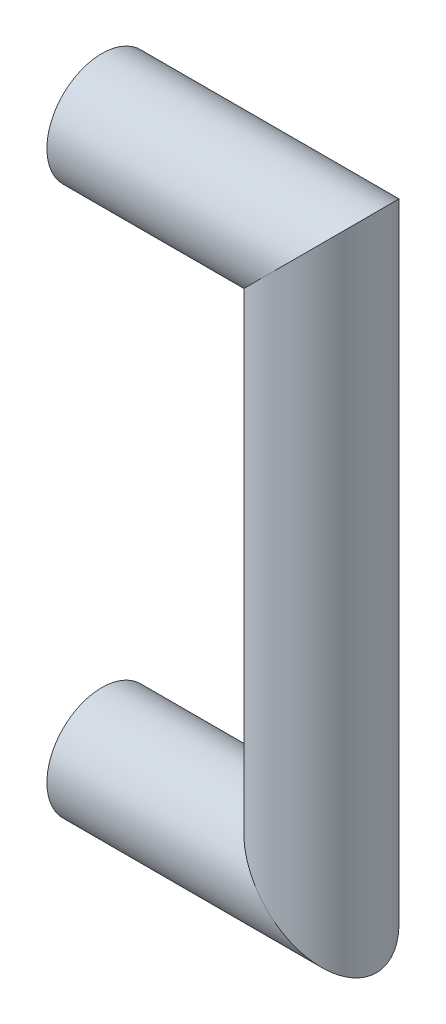
SolidWorks part; units mm, degrees
ref_plane "Front Plane" through (0, 0, 0) normal (0, 0, 1) x (1, 0, 0)
ref_plane "Top Plane" through (0, 0, 0) normal (0, 1, 0) x (1, 0, 0)
ref_plane "Right Plane" through (0, 0, 0) normal (1, 0, 0) x (0, 0, -1)
sketch "Sketch1" plane through (0, 0, 0) normal (1, 0, 0) x (0, 0, -1)
  circle A0 centre (0, 0) radius 10
  dimension "D1" = 20
sketch "Sketch3" plane through (0, 0, 0) normal (0, 0, 1) x (1, 0, 0)
  line L0 (0, 0) -> (40, 0)
  line L1 (40, 0) -> (40, -100)
  line L2 (40, -100) -> (0, -100)
  dimension "D1" = 40
  dimension "D2" = 100
sweep "Sweep1" add profiles "Sketch1" path "Sketch3"
